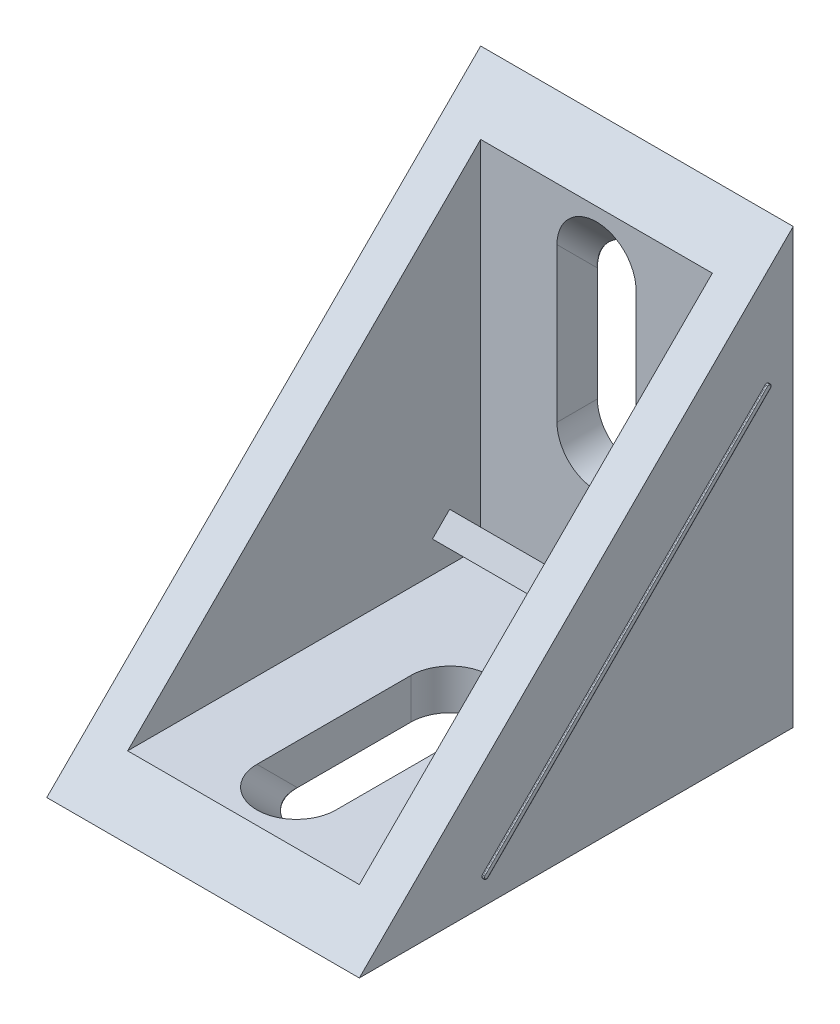
SolidWorks part; units mm, degrees
material "Plain Carbon Steel"
ref_plane "Front Plane" through (0, 0, 0) normal (0, 0, 1) x (1, 0, 0)
ref_plane "Top Plane" through (0, 0, 0) normal (0, 1, 0) x (1, 0, 0)
ref_plane "Right Plane" through (0, 0, 0) normal (1, 0, 0) x (0, 0, -1)
sketch "Sketch1" plane through (0, 0, 0) normal (1, 0, 0) x (0, 0, -1)
  line L0 (0, 0) -> (0, 23.6) construction
  line L1 (0, 0) -> (-23.6, 0) construction
  line L2 (-23.6, 0) -> (0, 23.6) construction
  line L3 (-11.8, 11.8) -> (0, 0) construction
  line L4 (0, 18.5) -> (-2.55, 21.05) construction
  line L5 (-21.05, 2.55) -> (-18.5, 0) construction
  point P3 (0, 0)
  point P5 (-21.05, 2.55)
  dimension "Length B" = 23.6
  dimension "Length A" = 23.6
  dimension "Hole 1 Draft Angle" = 45
  dimension "D1" = 18.5
  dimension "Hole 2 Draft Angle" = 45
  dimension "D2" = 5.1
sketch "Sketch2" plane through (0, 0, 0) normal (0, 0, 1) x (1, 0, 0)
  line L0 (-8.5, 0) -> (8.5, 0) construction
  line L1 (8.5, 0) -> (8.5, 2.2) construction
  line L2 (0, 0) -> (0, 23.6) construction
  line L3 (-8.6, 10.15) -> (8.6, 10.15) construction
  line L4 (-2.15, 16.35) -> (-2.15, 10.15) construction
  line L5 (2.15, 16.35) -> (2.15, 10.15) construction
  line L6 (0, 18.5) -> (0, 8) construction
  circle A0 centre (0, 10.15) radius 2.15 construction
  circle A1 centre (0, 16.35) radius 2.15 construction
  point P4 (0, 0)
  point P7 (8.5, 0)
  point P8 (0, 10.15)
  point P9 (0, 16.35)
  point P22 (0, 13.25)
  point P23 (0, 10.15)
  point P25 (8.6, 10.15)
  point P26 (-8.6, 10.15)
  dimension "Hole 1 Size" = 4.3
  dimension "Length C" = 17
  dimension "Hole Location 1" = 10.15
  dimension "Hole Location 2" = 6.2
  dimension "Thickness" = 2.2
  dimension "Overall Width" = 17.2
  dimension "Center" = 8.5
sketch "Sketch3" plane through (0, 0, 0) normal (0, 1, 0) x (1, 0, 0)
  line L0 (0, 0) -> (0, -23.6) construction
  line L1 (0, -11.8) -> (0, 0) construction
  line L2 (-2.15, -10.15) -> (-2.15, -16.35) construction
  line L3 (2.15, -10.15) -> (2.15, -16.35) construction
  line L4 (0, -8) -> (0, -18.5) construction
  circle A0 centre (0, -16.35) radius 2.15 construction
  circle A1 centre (0, -10.15) radius 2.15 construction
  point P0 (0, -23.6)
  point P10 (0, -8)
  point P12 (0, -20.7)
  point P13 (0, -18.5)
  point P20 (0, -13.25)
  dimension "Slot 2 Hole Size" = 4.3
  dimension "Slot 2 Hole to Hole Spacing" = 6.2
  dimension "Slot 2 Offset length" = 8
  dimension "Slot 2 Draft Length" = 12.7
  dimension "Slot 2 Length " = 10.5
sketch "Sketch4" plane through (0, 0, 0) normal (1, 0, 0) x (0, 0, -1)
  line L0 (0, 0) -> (-23.6, 0) construction
  line L1 (0, 0) -> (0, 23.6) construction
  line L2 (-23.6, 0) -> (0, 23.6) construction
  line L3 (0, 0) -> (-23.6, 0)
  line L4 (0, 0) -> (0, 23.6)
  line L5 (-23.6, 0) -> (0, 23.6)
extrude "Boss-Extrude1" add sketch "Sketch4" along normal up to vertex (8.5 mm away) and the other way up to vertex (8.5 mm away) up to point (8.5, 0, 0) other way up to point (-8.5, 0, 0)
shell "Shell1" thickness 2.2
ref_plane "Plane1" through (0, 0, 0) normal (0, 0.7071, -0.7071) x (1, 0, 0)
sketch "Sketch5" plane through (0, 0, 0) normal (0, 0.7071, -0.7071) x (1, 0, 0)
  line L0 (6.3, -3.1113) -> (-6.3, -3.1113) construction
  line L1 (6.3, -3.1113) -> (1.728, -3.1113)
  line L2 (6.3, -3.1113) -> (6.3, -6.1593)
  line L3 (1.728, -3.1113) -> (6.3, -6.1593)
  line L4 (0, 0) -> (0, -16.6877) construction
  line L5 (0, 0) -> (0, -16.6877) construction
  line L6 (-1.728, -3.1113) -> (-6.3, -6.1593)
  line L7 (-6.3, -3.1113) -> (-6.3, -6.1593)
  line L8 (-6.3, -3.1113) -> (-1.728, -3.1113)
  dimension "D1" = 3.048
  dimension "D2" = 4.572
extrude "Boss-Extrude2" add sketch "Sketch5" along normal mid plane 1.32
sketch "Sketch7" plane through (0, 0, 0) normal (0, -1, 0) x (1, 0, 0)
  circle A0 centre (0, 16.35) radius 2.15 construction
  circle A1 centre (0, 16.35) radius 2.15
sketch "Sketch8" plane through (0, 0, 0) normal (1, 0, 0) x (0, 0, -1)
  line L0 (-21.05, 2.55) -> (-18.5, 0) construction
  line L1 (-24.6421, 6.1421) -> (-18.5, 0)
  dimension "D1" = 5.08
sketch "Sketch9" plane through (0, 0, 0) normal (0, -1, 0) x (1, 0, 0)
  line L0 (-2.15, 10.15) -> (-2.15, 16.35) construction
  line L1 (2.15, 10.15) -> (2.15, 16.35) construction
  line L2 (-2.15, 10.15) -> (-2.15, 16.35)
  line L3 (2.15, 10.15) -> (2.15, 16.35)
  line L4 (0, 21.05) -> (0, 18.5) construction
  line L5 (0, 21.05) -> (0, 18.5) construction
  circle A0 centre (0, 10.15) radius 2.15 construction
  arc A2 (-2.15, 10.15) -> (2.15, 10.15) centre (0, 10.15) ccw
  circle A5 centre (0, 16.35) radius 2.15 construction
  arc A6 (2.15, 16.35) -> (-2.15, 16.35) centre (0, 16.35) ccw
  point P8 (0, 19.775)
extrude "Cut-Extrude1" cut sketch "Sketch9" against normal up to next
sketch "Sketch10" plane through (0, 2.2, 0) normal (0, 1, 0) x (1, 0, 0)
  line L0 (0, 0) -> (0, -23.6) construction
  line L1 (-2.15, -18.519) -> (-2.15, -16.35)
  line L2 (-2.15, -10.15) -> (-2.15, -16.35) construction
  line L3 (-2.15, -16.35) -> (2.15, -16.35)
  line L4 (2.15, -16.35) -> (2.15, -18.519)
  arc A0 (-2.15, -18.519) -> (2.15, -18.519) centre (0, -18.519) ccw
  point P11 (0, -20.669)
  dimension "D1" = 0.381
sweep "Cut-Sweep2" cut profiles "Sketch10" path "Sketch8"
sketch "Sketch11" plane through (0, 0, 0) normal (0, 0, -1) x (-1, 0, 0)
  line L0 (-2.15, 16.35) -> (-2.15, 10.15) construction
  line L1 (2.15, 16.35) -> (2.15, 10.15) construction
  line L2 (-2.15, 16.35) -> (-2.15, 10.15)
  line L3 (2.15, 16.35) -> (2.15, 10.15)
  circle A0 centre (0, 10.15) radius 2.15 construction
  circle A1 centre (0, 16.35) radius 2.15 construction
  arc A2 (-2.15, 10.15) -> (2.15, 10.15) centre (0, 10.15) ccw
  arc A3 (2.15, 16.35) -> (-2.15, 16.35) centre (0, 16.35) ccw
extrude "Cut-Extrude2" cut sketch "Sketch11" against normal up to next
sketch "Sketch12" plane through (0, 0, 2.2) normal (0, 0, 1) x (1, 0, 0)
  line L0 (0, 18.5) -> (0, 21.05) construction
  line L1 (-2.15, 18.519) -> (-2.15, 16.35)
  line L2 (-2.15, 16.35) -> (-2.15, 10.15) construction
  line L3 (2.15, 18.519) -> (2.15, 16.35)
  line L4 (2.15, 16.35) -> (-2.15, 16.35)
  arc A0 (2.15, 18.519) -> (-2.15, 18.519) centre (0, 18.519) ccw
  point P14 (0, 20.669)
  dimension "D1" = 0.381
sketch "Sketch13" plane through (0, 0, 0) normal (1, 0, 0) x (0, 0, -1)
  line L0 (0, 18.5) -> (-2.55, 21.05) construction
  line L1 (0, 18.5) -> (-2.55, 21.05)
sweep "Cut-Sweep3" cut profiles "Sketch12" path "Sketch13"
sketch "Sketch14" plane through (8.5, 0, 0) normal (1, 0, 0) x (0, 0, -1)
  line L1 (0, 23.6) -> (-23.6, 0) construction
  line L2 (2.6941, 20.9059) -> (-20.9059, -2.6941)
  line L3 (-1.3277, 16.8841) -> (-16.8841, 1.3277)
  line L4 (-9.1059, 9.1059) -> (-11.8, 11.8) construction
  point P0 (-9.1059, 9.1059)
  point P5 (-11.8, 11.8)
  dimension "D2" = 22
  dimension "D1" = 3.81
extrude "Extrude-Thin1" add sketch "Sketch14" along normal up to vertex (0.1 mm away) thin up to point (8.6, 10.15, 0) thin type mid plane wall 0.3048
fillet "Fillet1" radius 0.127 4 edges at (8.55, 1.22, 16.7763) (8.55, 1.4355, 16.9919) (8.55, 16.9919, 1.4355) (8.55, 16.7763, 1.22)
fillet "Fillet2" radius 0.0508 8 edges at (8.6, 1.4355, 16.9393) (8.6, 9.2137, 9.2137) (8.6, 16.9393, 1.4355) (8.6, 16.7763, 1.2726) (8.6, 8.9982, 8.9982) (8.6, 1.2726, 16.7763) (8.6, 1.3277, 16.8841) (8.6, 16.8841, 1.3277)
mirror "Mirror1" about plane through (0, 0, 0) normal (1, 0, 0) of "Fillet2", "Fillet1", "Extrude-Thin1"
equation "\"Length A@Sketch1\" = \"Length B@Sketch1\""
equation "\"D1@Shell1\"=\"Thickness@Sketch2\""
equation "\"D1@Boss-Extrude2\"=\"Thickness@Sketch2\"*.6"
